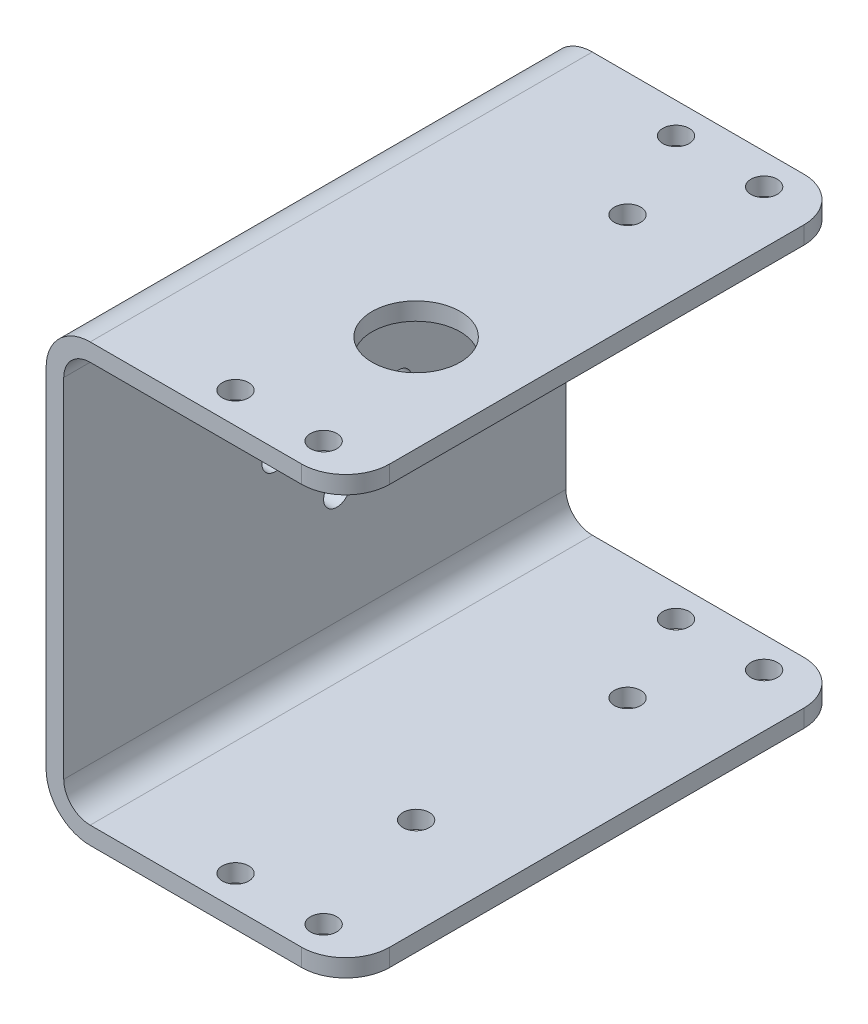
SolidWorks part; units mm, degrees
ref_plane "前视基准面" through (0, 0, 0) normal (0, 0, 1) x (1, 0, 0)
ref_plane "上视基准面" through (0, 0, 0) normal (0, 1, 0) x (1, 0, 0)
ref_plane "右视基准面" through (0, 0, 0) normal (1, 0, 0) x (0, 0, -1)
sketch "草图1" plane through (0, 0, 0) normal (0, 0, 1) x (1, 0, 0)
  line L1 (-17, -24.75) -> (17, -24.75)
  line L2 (-17, -24.75) -> (-17, 24.75)
  line L3 (-17, 24.75) -> (17, 24.75)
  line L4 (17, -24.75) -> (17, -22.75)
  line L7 (-15, -22.75) -> (-15, 22.75)
  line L8 (15, -22.75) -> (15, 22.75) construction
  line L9 (-15, 22.75) -> (15, 22.75) construction
  line L10 (-15, -22.75) -> (15, -22.75) construction
  line L11 (-15, 22.75) -> (17, 22.75)
  line L12 (-15, -22.75) -> (17, -22.75)
  line L13 (17, 22.75) -> (17, 24.75)
  line L15 (17, -24.75) -> (17, 24.75) construction
  point P0 (0, 0)
extrude "凸台-拉伸1" add sketch "草图1" along normal blind 57
sketch "草图2" plane through (0, 24.75, 0) normal (0, 1, 0) x (1, 0, 0)
  line L0 (17, 0) -> (-17, 0) construction
  circle A0 centre (6, -14) radius 1.5
  circle A1 centre (6, -38) radius 1.5
extrude "切除-拉伸1" cut sketch "草图2" against normal blind 57
sketch "草图4" plane through (-17, 0, 0) normal (-1, 0, 0) x (0, 0, 1)
  circle A0 centre (26, 0) radius 4
  circle A1 centre (26, 7) radius 1.5
  circle A2 centre (33, 0) radius 1.5
  circle A3 centre (26, -7) radius 1.5
  circle A4 centre (19, 0) radius 1.5
  point P13 (26, 0)
  dimension "D1" = 4
extrude "切除-拉伸2" cut sketch "草图4" against normal blind 57
fillet "圆角1" radius 5 2 edges at (-17, -24.75, 28.5) (-17, 24.75, 28.5)
fillet "圆角2" radius 3 2 edges at (-15, -22.75, 28.5) (-15, 22.75, 28.5)
fillet "圆角3" radius 5 4 edges at (17, 23.75, 0) (17, -23.75, 0) (17, 23.75, 57) (17, -23.75, 57)
sketch "草图5" plane through (0, 24.75, 0) normal (0, 1, 0) x (1, 0, 0)
  circle A0 centre (6, -38) radius 5
extrude "切除-拉伸3" cut sketch "草图5" against normal blind 26
sketch "草图6" plane through (0, -24.75, 0) normal (0, -1, 0) x (1, 0, 0)
  circle A0 centre (1, 53.5) radius 1.5
  circle A1 centre (11, 53.5) radius 1.5
  circle A2 centre (11, 3.5) radius 1.5
  circle A3 centre (1, 3.5) radius 1.5
extrude "切除-拉伸4" cut sketch "草图6" against normal blind 71
